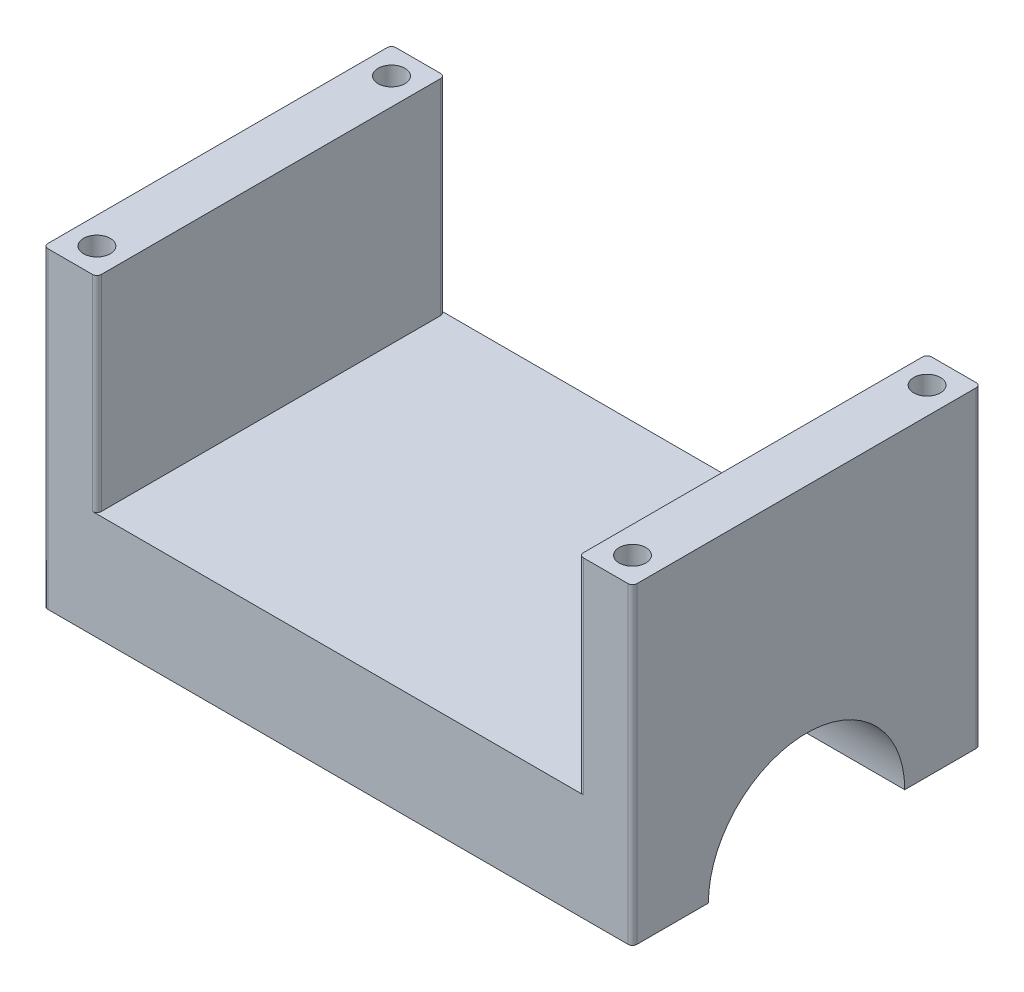
SolidWorks part; units mm, degrees
ref_plane "Front Plane" through (0, 0, 0) normal (0, 0, 1) x (1, 0, 0)
ref_plane "Top Plane" through (0, 0, 0) normal (0, 1, 0) x (1, 0, 0)
ref_plane "Right Plane" through (0, 0, 0) normal (1, 0, 0) x (0, 0, -1)
sketch "Sketch1" plane through (0, 0, 0) normal (0, 1, 0) x (1, 0, 0)
  line L1 (0, 0) -> (66, 0)
  line L2 (0, 0) -> (0, 39)
  line L3 (0, 39) -> (66, 39)
  line L4 (66, 0) -> (66, 39)
  point P4 (0, 0)
  dimension "D1" = 66
  dimension "D2" = 39
extrude "Boss-Extrude1" add sketch "Sketch1" along normal blind 35
sketch "Sketch3" plane through (0, 35, 0) normal (0, 1, 0) x (1, 0, 0)
  line L0 (66, 39) -> (0, 39) construction
  line L1 (6, 0) -> (60, 0)
  line L2 (6, 0) -> (6, 39)
  line L3 (6, 39) -> (60, 39)
  line L4 (60, 0) -> (60, 39)
  line L5 (0, 0) -> (66, 0) construction
  dimension "D1" = 6
  dimension "D2" = 6
extrude "Cut-Extrude1" cut sketch "Sketch3" against normal offset from surface (23 mm away) 23 up to face at (33, 35, -19.5)
sketch "Sketch4" plane through (66, 0, 0) normal (1, 0, 0) x (0, 0, -1)
  line L0 (0, 0) -> (39, 0) construction
  circle A0 centre (19.5, 0) radius 11
  dimension "D1" = 22
extrude "Cut-Extrude2" cut sketch "Sketch4" against normal through all
sketch "Sketch5" plane through (0, 35, 0) normal (0, 1, 0) x (1, 0, 0)
  circle A0 centre (3, 36) radius 1.5
  circle A1 centre (3, 3) radius 1.5
  circle A2 centre (63, 36) radius 1.5
  circle A3 centre (63, 3) radius 1.5
  point P8 (0, 0)
  point P10 (0, 0)
  point P11 (0, 0)
  point P13 (0, 0)
  point P14 (0, 0)
  point P15 (63.3629, 34.8941)
  point P16 (0, 0)
  point P17 (0, 0)
  dimension "D1" = 3
  dimension "D2" = 3
  dimension "D3" = 3
  dimension "D4" = 3
  dimension "D5" = 3
  dimension "D6" = 3
  dimension "D7" = 3
  dimension "D8" = 3
extrude "Cut-Extrude3" cut sketch "Sketch5" against normal through all contours A1 | A3 | A2 | A0
fillet "Fillet2" radius 0.5 8 edges at (60, 23.5, -39) (66, 17.5, -39) (66, 17.5, 0) (60, 23.5, 0) (6, 23.5, -39) (6, 23.5, 0) (0, 17.5, 0) (0, 17.5, -39)
